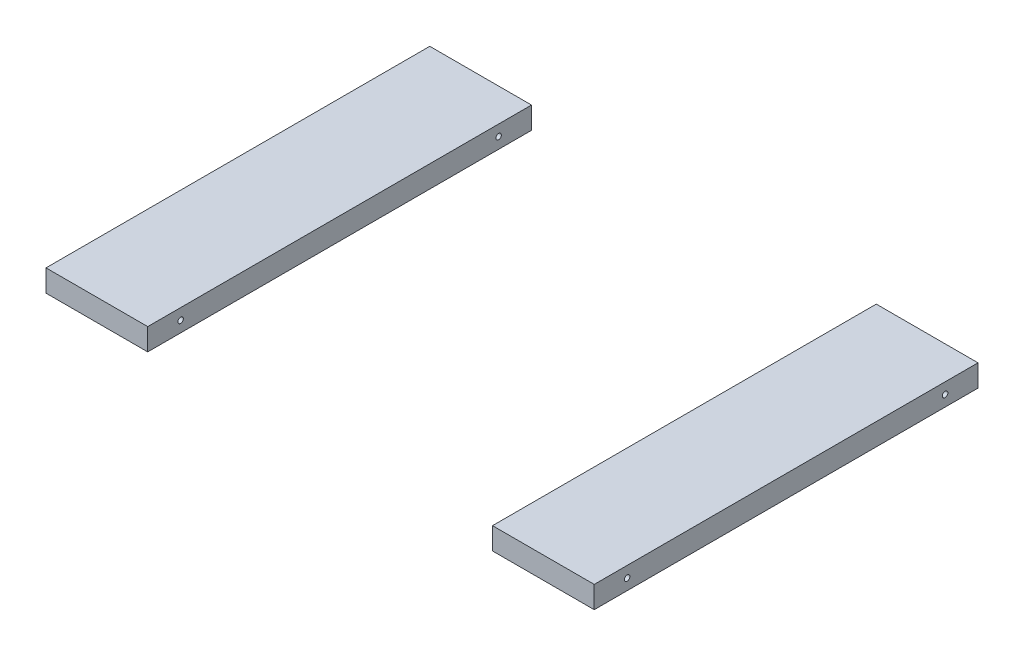
SolidWorks part; units mm, degrees
ref_plane "Front Plane" through (0, 0, 0) normal (0, 0, 1) x (1, 0, 0)
ref_plane "Top Plane" through (0, 0, 0) normal (0, 1, 0) x (1, 0, 0)
ref_plane "Right Plane" through (0, 0, 0) normal (1, 0, 0) x (0, 0, -1)
sketch "Sketch1" plane through (0, 0, 0) normal (0, 1, 0) x (1, 0, 0)
  line L1 (-250, 175) -> (250, 175)
  line L2 (-250, 175) -> (-250, -175)
  line L3 (-250, -175) -> (250, -175)
  line L4 (250, 175) -> (250, -175)
  line L5 (-250, 175) -> (250, -175) construction
  line L6 (-250, -175) -> (250, 175) construction
  point P0 (0, 0)
  dimension "D1" = 350
  dimension "D2" = 500
extrude "Boss-Extrude1" add sketch "Sketch1" along normal blind 20
sketch "Sketch2" plane through (0, 20, 0) normal (0, 1, 0) x (1, 0, 0)
  line L0 (-250, -175) -> (250, -175) construction
  line L1 (-157.224, 175) -> (157.224, 175)
  line L2 (-157.224, 175) -> (-157.224, -175)
  line L3 (-157.224, -175) -> (157.224, -175)
  line L4 (157.224, 175) -> (157.224, -175)
  line L5 (-157.224, 175) -> (157.224, -175) construction
  line L6 (-157.224, -175) -> (157.224, 175) construction
  point P0 (0, 0)
extrude "Cut-Extrude1" cut sketch "Sketch2" against normal through all
sketch "Sketch4" plane through (250, 0, 0) normal (1, 0, 0) x (0, 0, -1)
  line L0 (-175, 20) -> (175, 20) construction
  line L1 (-175, 20) -> (-175, 0) construction
  circle A0 centre (-145, 10) radius 2.5
  circle A1 centre (145, 10) radius 2.5
  point P8 (-175, 10)
  dimension "D1" = 10
  dimension "D2" = 5
  dimension "D3" = 10
  dimension "D4" = 290
  dimension "D5" = 30
extrude "Cut-Extrude2" cut sketch "Sketch4" against normal through all
